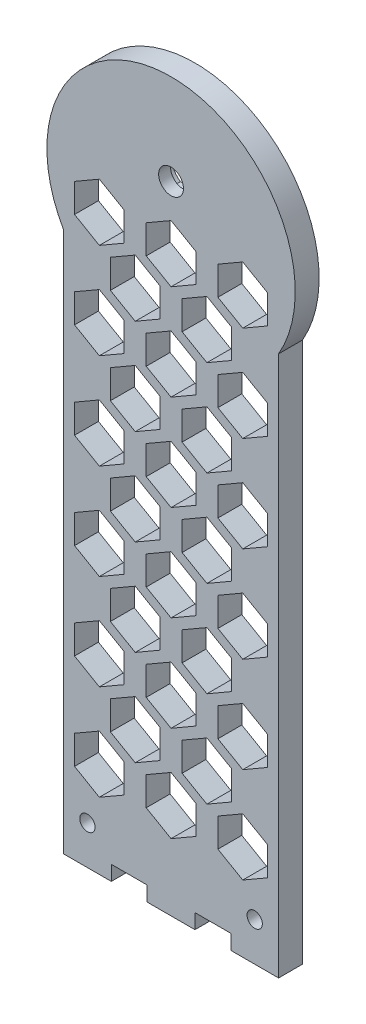
SolidWorks part; units mm, degrees
ref_plane "前视基准面" through (0, 0, 0) normal (0, 0, 1) x (1, 0, 0)
ref_plane "上视基准面" through (0, 0, 0) normal (0, 1, 0) x (1, 0, 0)
ref_plane "右视基准面" through (0, 0, 0) normal (1, 0, 0) x (0, 0, -1)
other "Configuration Table"
sketch "草图1" plane through (0, 0, 0) normal (0, 0, 1) x (1, 0, 0)
  line L0 (0, 0) -> (45, 0)
  line L1 (45, 0) -> (45, 113.1)
  line L2 (0, 0) -> (0, 113.1)
  line L3 (22.5, 126.0904) -> (22.5, 0) construction
  line L4 (0, 113.1) -> (22.5, 126.0904) construction
  line L5 (22.5, 126.0904) -> (45, 113.1) construction
  line L6 (0, 113.1) -> (45, 113.1) construction
  line L7 (19.44, 129.02) -> (25.56, 129.02)
  line L8 (22.5, 133.1) -> (22.5, 126.0904) construction
  arc A1 (0, 113.1) -> (45, 113.1) centre (22.5, 126.0904) cw
  arc A2 (25.56, 129.02) -> (19.44, 129.02) centre (22.5, 133.1) ccw
  dimension "D3" = 120
  dimension "D5" = 5.1
  dimension "D1" = 45
  dimension "D2" = 113.1
  dimension "D4" = 20
  dimension "D6" = 4.08
  dimension "D7" = 6.12
extrude "凸台-拉伸1" add sketch "草图1" along normal blind 5
sketch "草图2" plane through (0, 0, 5) normal (0, 0, 1) x (1, 0, 0)
  line L0 (0, 0) -> (45, 0) construction
  line L1 (27.5, 0) -> (35, 0)
  line L2 (27.5, 0) -> (27.5, 3.1)
  line L3 (27.5, 3.1) -> (35, 3.1)
  line L4 (35, 0) -> (35, 3.1)
  line L5 (0, 113.1) -> (0, 0) construction
  line L6 (10, 0) -> (17.5, 0)
  line L7 (10, 0) -> (10, 3.1)
  line L8 (10, 3.1) -> (17.5, 3.1)
  line L9 (17.5, 0) -> (17.5, 3.1)
  line L10 (45, 0) -> (45, 113.1) construction
  line L11 (7.5, 20) -> (22.5, 20) construction
  line L12 (7.5, 26) -> (2.3038, 23)
  line L13 (2.3038, 23) -> (2.3038, 17)
  line L14 (2.3038, 17) -> (7.5, 14)
  line L15 (7.5, 14) -> (12.6962, 17)
  line L16 (12.6962, 17) -> (12.6962, 23)
  line L17 (12.6962, 23) -> (7.5, 26)
  line L18 (22.5, 26) -> (17.3038, 23)
  line L19 (17.3038, 23) -> (17.3038, 17)
  line L20 (17.3038, 17) -> (22.5, 14)
  line L21 (22.5, 14) -> (27.6962, 17)
  line L22 (27.6962, 17) -> (27.6962, 23)
  line L23 (27.6962, 23) -> (22.5, 26)
  line L24 (37.5, 26) -> (32.3038, 23)
  line L25 (32.3038, 23) -> (32.3038, 17)
  line L26 (32.3038, 17) -> (37.5, 14)
  line L27 (37.5, 14) -> (42.6962, 17)
  line L28 (42.6962, 17) -> (42.6962, 23)
  line L29 (42.6962, 23) -> (37.5, 26)
  line L30 (22.5, 20) -> (37.5, 20) construction
  line L43 (15, 56) -> (9.8038, 53)
  line L44 (15, 36) -> (9.8038, 33)
  line L45 (9.8038, 33) -> (9.8038, 27)
  line L46 (9.8038, 27) -> (15, 24)
  line L47 (15, 24) -> (20.1962, 27)
  line L48 (20.1962, 27) -> (20.1962, 33)
  line L49 (20.1962, 33) -> (15, 36)
  line L50 (30, 36) -> (24.8038, 33)
  line L51 (24.8038, 33) -> (24.8038, 27)
  line L52 (24.8038, 27) -> (30, 24)
  line L53 (30, 24) -> (35.1962, 27)
  line L54 (35.1962, 27) -> (35.1962, 33)
  line L55 (35.1962, 33) -> (30, 36)
  line L56 (9.8038, 53) -> (9.8038, 47)
  line L57 (9.8038, 47) -> (15, 44)
  line L58 (15, 44) -> (20.1962, 47)
  line L59 (20.1962, 47) -> (20.1962, 53)
  line L60 (20.1962, 53) -> (15, 56)
  line L61 (30, 56) -> (24.8038, 53)
  line L62 (24.8038, 53) -> (24.8038, 47)
  line L63 (24.8038, 47) -> (30, 44)
  line L64 (30, 44) -> (35.1962, 47)
  line L65 (35.1962, 47) -> (35.1962, 53)
  line L66 (35.1962, 53) -> (30, 56)
  line L67 (37.5, 46) -> (32.3038, 43)
  line L68 (32.3038, 43) -> (32.3038, 37)
  line L69 (32.3038, 37) -> (37.5, 34)
  line L70 (37.5, 34) -> (42.6962, 37)
  line L71 (42.6962, 37) -> (42.6962, 43)
  line L72 (42.6962, 43) -> (37.5, 46)
  line L73 (22.5, 46) -> (17.3038, 43)
  line L74 (17.3038, 43) -> (17.3038, 37)
  line L75 (17.3038, 37) -> (22.5, 34)
  line L76 (22.5, 34) -> (27.6962, 37)
  line L77 (27.6962, 37) -> (27.6962, 43)
  line L78 (27.6962, 43) -> (22.5, 46)
  line L79 (7.5, 46) -> (2.3038, 43)
  line L80 (2.3038, 43) -> (2.3038, 37)
  line L81 (2.3038, 37) -> (7.5, 34)
  line L82 (7.5, 34) -> (12.6962, 37)
  line L83 (12.6962, 37) -> (12.6962, 43)
  line L84 (12.6962, 43) -> (7.5, 46)
  line L85 (15, 76) -> (9.8038, 73)
  line L86 (9.8038, 73) -> (9.8038, 67)
  line L87 (9.8038, 67) -> (15, 64)
  line L88 (15, 64) -> (20.1962, 67)
  line L89 (20.1962, 67) -> (20.1962, 73)
  line L90 (20.1962, 73) -> (15, 76)
  line L91 (30, 76) -> (24.8038, 73)
  line L92 (24.8038, 73) -> (24.8038, 67)
  line L93 (24.8038, 67) -> (30, 64)
  line L94 (30, 64) -> (35.1962, 67)
  line L95 (35.1962, 67) -> (35.1962, 73)
  line L96 (35.1962, 73) -> (30, 76)
  line L97 (37.5, 66) -> (32.3038, 63)
  line L98 (32.3038, 63) -> (32.3038, 57)
  line L99 (32.3038, 57) -> (37.5, 54)
  line L100 (37.5, 54) -> (42.6962, 57)
  line L101 (42.6962, 57) -> (42.6962, 63)
  line L102 (42.6962, 63) -> (37.5, 66)
  line L103 (22.5, 66) -> (17.3038, 63)
  line L104 (17.3038, 63) -> (17.3038, 57)
  line L105 (17.3038, 57) -> (22.5, 54)
  line L106 (22.5, 54) -> (27.6962, 57)
  line L107 (27.6962, 57) -> (27.6962, 63)
  line L108 (27.6962, 63) -> (22.5, 66)
  line L109 (7.5, 66) -> (2.3038, 63)
  line L110 (2.3038, 63) -> (2.3038, 57)
  line L111 (2.3038, 57) -> (7.5, 54)
  line L112 (7.5, 54) -> (12.6962, 57)
  line L113 (12.6962, 57) -> (12.6962, 63)
  line L114 (12.6962, 63) -> (7.5, 66)
  line L115 (15, 96) -> (9.8038, 93)
  line L116 (9.8038, 93) -> (9.8038, 87)
  line L117 (9.8038, 87) -> (15, 84)
  line L118 (15, 84) -> (20.1962, 87)
  line L119 (20.1962, 87) -> (20.1962, 93)
  line L120 (20.1962, 93) -> (15, 96)
  line L121 (30, 96) -> (24.8038, 93)
  line L122 (24.8038, 93) -> (24.8038, 87)
  line L123 (24.8038, 87) -> (30, 84)
  line L124 (30, 84) -> (35.1962, 87)
  line L125 (35.1962, 87) -> (35.1962, 93)
  line L126 (35.1962, 93) -> (30, 96)
  line L127 (37.5, 86) -> (32.3038, 83)
  line L128 (32.3038, 83) -> (32.3038, 77)
  line L129 (32.3038, 77) -> (37.5, 74)
  line L130 (37.5, 74) -> (42.6962, 77)
  line L131 (42.6962, 77) -> (42.6962, 83)
  line L132 (42.6962, 83) -> (37.5, 86)
  line L133 (22.5, 86) -> (17.3038, 83)
  line L134 (17.3038, 83) -> (17.3038, 77)
  line L135 (17.3038, 77) -> (22.5, 74)
  line L136 (22.5, 74) -> (27.6962, 77)
  line L137 (27.6962, 77) -> (27.6962, 83)
  line L138 (27.6962, 83) -> (22.5, 86)
  line L139 (7.5, 86) -> (2.3038, 83)
  line L140 (2.3038, 83) -> (2.3038, 77)
  line L141 (2.3038, 77) -> (7.5, 74)
  line L142 (7.5, 74) -> (12.6962, 77)
  line L143 (12.6962, 77) -> (12.6962, 83)
  line L144 (12.6962, 83) -> (7.5, 86)
  line L145 (15, 116) -> (9.8038, 113)
  line L146 (9.8038, 113) -> (9.8038, 107)
  line L147 (9.8038, 107) -> (15, 104)
  line L148 (15, 104) -> (20.1962, 107)
  line L149 (20.1962, 107) -> (20.1962, 113)
  line L150 (20.1962, 113) -> (15, 116)
  line L151 (30, 116) -> (24.8038, 113)
  line L152 (24.8038, 113) -> (24.8038, 107)
  line L153 (24.8038, 107) -> (30, 104)
  line L154 (30, 104) -> (35.1962, 107)
  line L155 (35.1962, 107) -> (35.1962, 113)
  line L156 (35.1962, 113) -> (30, 116)
  line L157 (37.5, 106) -> (32.3038, 103)
  line L158 (32.3038, 103) -> (32.3038, 97)
  line L159 (32.3038, 97) -> (37.5, 94)
  line L160 (37.5, 94) -> (42.6962, 97)
  line L161 (42.6962, 97) -> (42.6962, 103)
  line L162 (42.6962, 103) -> (37.5, 106)
  line L163 (22.5, 106) -> (17.3038, 103)
  line L164 (17.3038, 103) -> (17.3038, 97)
  line L165 (17.3038, 97) -> (22.5, 94)
  line L166 (22.5, 94) -> (27.6962, 97)
  line L167 (27.6962, 97) -> (27.6962, 103)
  line L168 (27.6962, 103) -> (22.5, 106)
  line L169 (7.5, 106) -> (2.3038, 103)
  line L170 (2.3038, 103) -> (2.3038, 97)
  line L171 (2.3038, 97) -> (7.5, 94)
  line L172 (7.5, 94) -> (12.6962, 97)
  line L173 (12.6962, 97) -> (12.6962, 103)
  line L174 (12.6962, 103) -> (7.5, 106)
  line L175 (7.5, 126) -> (2.3038, 123)
  line L176 (2.3038, 123) -> (2.3038, 117)
  line L177 (2.3038, 117) -> (7.5, 114)
  line L178 (7.5, 114) -> (12.6962, 117)
  line L179 (12.6962, 117) -> (12.6962, 123)
  line L180 (12.6962, 123) -> (7.5, 126)
  line L181 (22.5, 126) -> (17.3038, 123)
  line L182 (17.3038, 123) -> (17.3038, 117)
  line L183 (17.3038, 117) -> (22.5, 114)
  line L184 (22.5, 114) -> (27.6962, 117)
  line L185 (27.6962, 117) -> (27.6962, 123)
  line L186 (27.6962, 123) -> (22.5, 126)
  line L187 (37.5, 126) -> (32.3038, 123)
  line L188 (32.3038, 123) -> (32.3038, 117)
  line L189 (32.3038, 117) -> (37.5, 114)
  line L190 (37.5, 114) -> (42.6962, 117)
  line L191 (42.6962, 117) -> (42.6962, 123)
  line L192 (42.6962, 123) -> (37.5, 126)
  circle A0 centre (40, 8.1) radius 1.6
  circle A1 centre (5, 8.1) radius 1.6
  circle A2 centre (7.5, 20) radius 5.1962 construction
  circle A3 centre (22.5, 20) radius 5.1962 construction
  circle A4 centre (37.5, 20) radius 5.1962 construction
  circle A5 centre (15, 30) radius 5.1962 construction
  circle A6 centre (30, 30) radius 5.1962 construction
  dimension "D7" = 3.2
  dimension "D1" = 3.1
  dimension "D2" = 3.1
  dimension "D3" = 10
  dimension "D4" = 10
  dimension "D5" = 10
  dimension "D6" = 7.5
  dimension "D8" = 5
  dimension "D9" = 5
  dimension "D10" = 5
  dimension "D11" = 5
  dimension "D12" = 22.5
  dimension "D13" = 15
  dimension "D14" = 15
  dimension "D15" = 6
  dimension "D16" = 20
  dimension "D17" = 15
  dimension "D18" = 15
  dimension "D19" = 30
  dimension "D20" = 30
  dimension "D21" = 5
  dimension "D22" = 2
extrude "切除-拉伸1" cut sketch "草图2" against normal up to next (5 mm away)
sketch "草图3" plane through (0, 0, 5) normal (0, 0, 1) x (1, 0, 0)
  line L0 (19.44, 129.02) -> (25.56, 129.02)
  arc A0 (19.44, 129.02) -> (25.56, 129.02) centre (22.5, 133.1) cw
  circle A1 centre (22.5, 133.1) radius 2.6
  dimension "D1" = 5.2
extrude "凸台-拉伸2" add sketch "草图3" against normal blind 2.5
